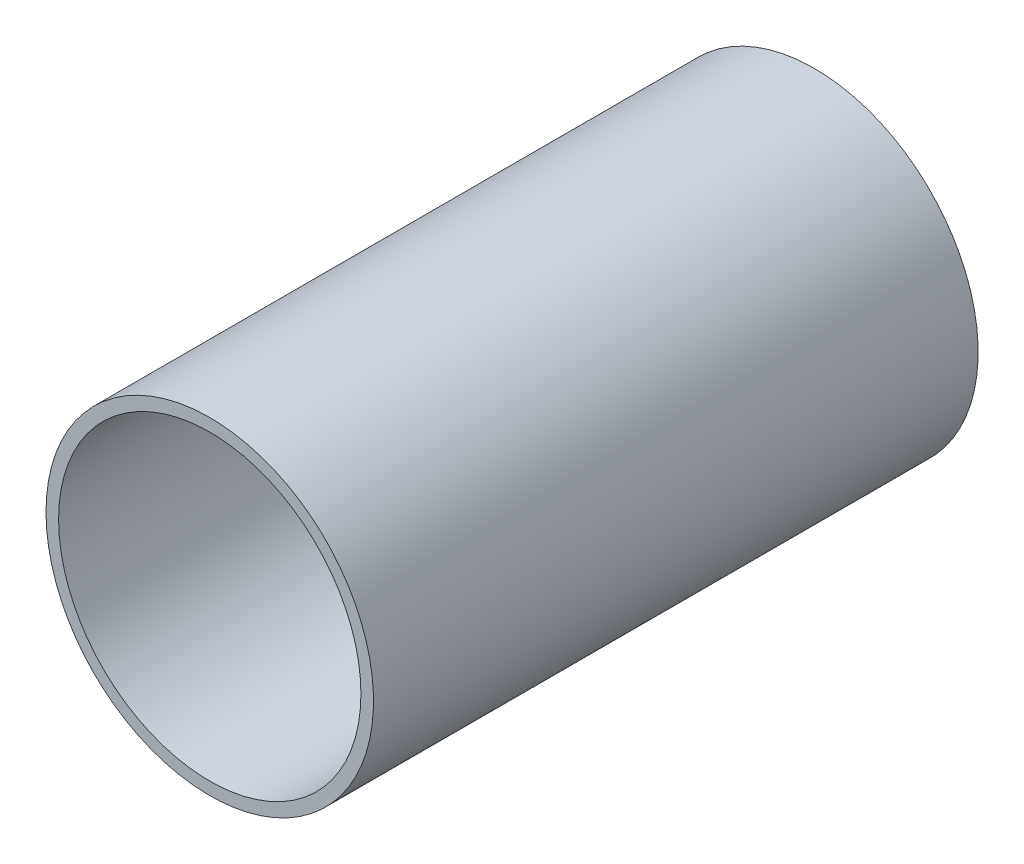
SolidWorks part; units mm, degrees
material "Acrylic (Medium-high impact)"
ref_plane "Front Plane" through (0, 0, 0) normal (0, 0, 1) x (1, 0, 0)
ref_plane "Top Plane" through (0, 0, 0) normal (0, 1, 0) x (1, 0, 0)
ref_plane "Right Plane" through (0, 0, 0) normal (1, 0, 0) x (0, 0, -1)
sketch "Sketch1" plane through (0, 0, 0) normal (0, 0, 1) x (1, 0, 0)
  circle A0 centre (0, 0) radius 76.2
  dimension "D1" = 152.4
extrude "Extrude-Thin1" add sketch "Sketch1" along normal mid plane 304.8 thin
